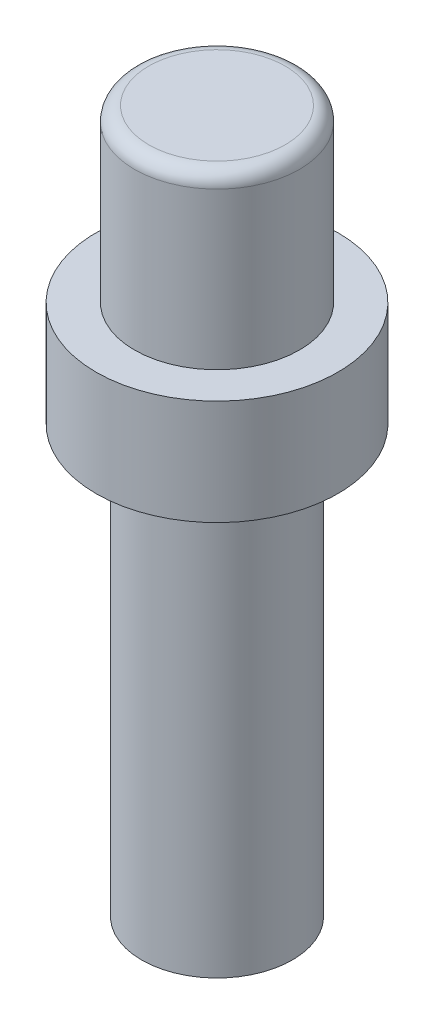
SolidWorks part; units mm, degrees
ref_plane "Front Plane" through (0, 0, 0) normal (0, 0, 1) x (1, 0, 0)
ref_plane "Top Plane" through (0, 0, 0) normal (0, 1, 0) x (1, 0, 0)
ref_plane "Right Plane" through (0, 0, 0) normal (1, 0, 0) x (0, 0, -1)
sketch "Sketch1" plane through (0, 0, 0) normal (0, 1, 0) x (1, 0, 0)
  circle A0 centre (0, 0) radius 2.65
  dimension "D1" = 5.3
extrude "Boss-Extrude1" add sketch "Sketch1" along normal blind 15
sketch "Sketch2" plane through (0, 0, 0) normal (0, -1, 0) x (1, 0, 0)
  circle A0 centre (0, 0) radius 1.15
  dimension "D1" = 2.3
extrude "Cut-Extrude1" cut sketch "Sketch2" against normal blind 12
sketch "Sketch3" plane through (0, 15, 0) normal (0, 1, 0) x (1, 0, 0)
  circle A0 centre (0, 0) radius 4.25
  dimension "D1" = 8.5
extrude "Boss-Extrude2" add sketch "Sketch3" along normal blind 3.7
sketch "Sketch4" plane through (0, 18.7, 0) normal (0, 1, 0) x (1, 0, 0)
  circle A0 centre (0, 0) radius 2.9
  dimension "D1" = 5.8
extrude "Boss-Extrude3" add sketch "Sketch4" along normal blind 6
fillet "Fillet2" radius 0.5 1 edges at (0, 24.7, 2.9)
